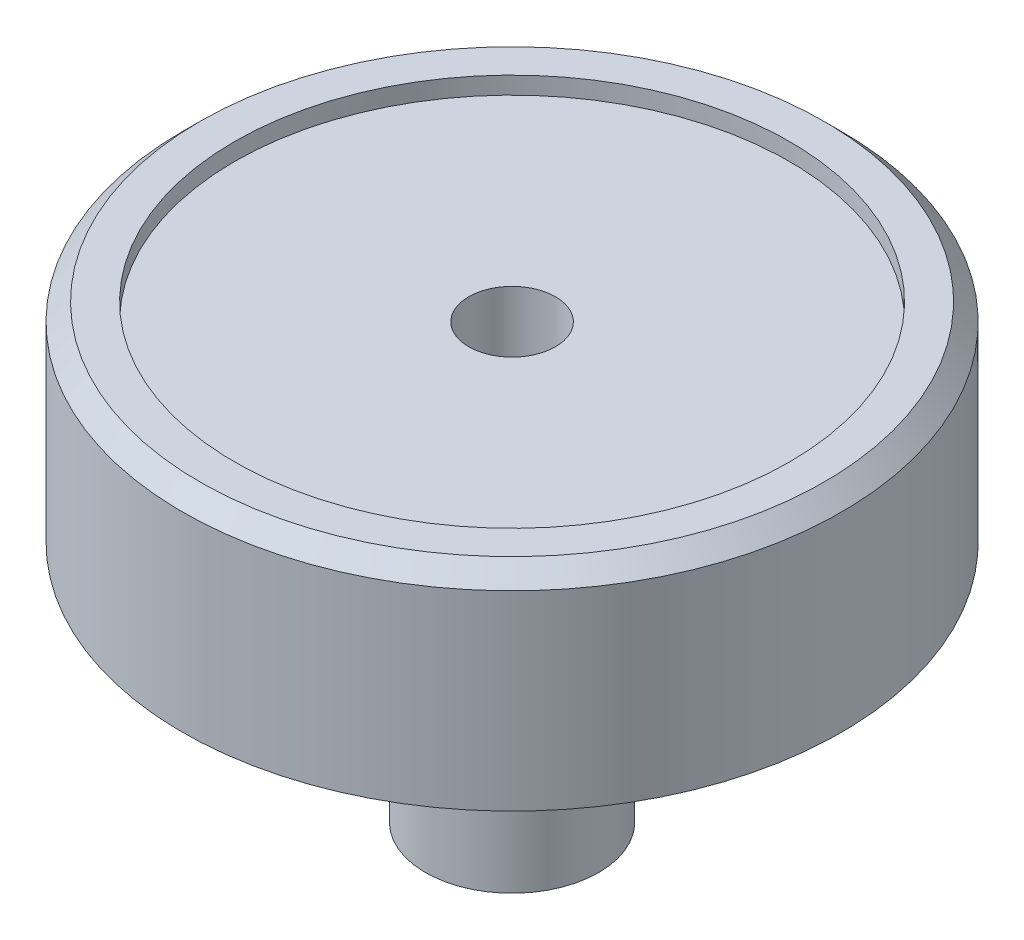
SolidWorks part; units mm, degrees
material "ABS"
ref_plane "Спереди" through (0, 0, 0) normal (0, 0, 1) x (1, 0, 0)
ref_plane "Сверху" through (0, 0, 0) normal (0, 1, 0) x (1, 0, 0)
ref_plane "Справа" through (0, 0, 0) normal (1, 0, 0) x (0, 0, -1)
sketch "Эскиз2" plane through (0, 0, 0) normal (0, 0, 1) x (1, 0, 0)
  line L1 (0, 4.5) -> (-9.5, 4.5)
  line L2 (-9.5, 4.5) -> (-9.5, -1.5)
  line L5 (-9.5, -1.5) -> (-6, -1.5)
  line L6 (-6, 0) -> (0, 0)
  line L7 (0, 4.5) -> (0, 0)
  line L8 (-6, -1.5) -> (-6, 0)
  dimension "D2" = 9.5
  dimension "D3" = 1.5
  dimension "D4" = 6
  dimension "D6" = 6
revolve "База" add sketch "Эскиз2" angle 360 about L7
chamfer "Фаска1" distance 0.5 angle 45 1 edges at (-9.5, 4.5, 0)
sketch "Эскиз8" plane through (0, 0, 0) normal (0, -1, 0) x (1, 0, 0)
  line L1 (-1.175, 3.175) -> (1.175, 3.175)
  line L2 (-3.175, 1.175) -> (-3.175, -1.175)
  line L3 (-1.175, -3.175) -> (1.175, -3.175)
  line L4 (3.175, 1.175) -> (3.175, -1.175)
  line L5 (-3.175, 3.175) -> (3.175, -3.175) construction
  line L6 (-3.175, -3.175) -> (3.175, 3.175) construction
  arc A0 (-3.175, -1.175) -> (-1.175, -3.175) centre (-1.175, -1.175) ccw
  arc A1 (1.175, -3.175) -> (3.175, -1.175) centre (1.175, -1.175) ccw
  arc A2 (1.175, 3.175) -> (3.175, 1.175) centre (1.175, 1.175) cw
  arc A3 (-1.175, 3.175) -> (-3.175, 1.175) centre (-1.175, 1.175) ccw
  point P0 (0, 0)
  dimension "D2" = 2
  dimension "D1" = 6.35
extrude "Направляющая" add sketch "Эскиз8" along normal blind 5.5
sketch "Эскиз6" plane through (0, 4.5, 0) normal (0, 1, 0) x (1, 0, 0)
  circle A0 centre (0, 0) radius 8
  dimension "D1" = 16
extrude "Основание пластины" cut sketch "Эскиз6" against normal blind 0.5
sketch "Эскиз9" plane through (0, -5.5, 0) normal (0, -1, 0) x (1, 0, 0)
  circle A0 centre (0, 0) radius 2.5
  dimension "D1" = 5
extrude "Продолжение направляющей" add sketch "Эскиз9" along normal blind 3
hole_wizard "Отверстие M2,5" positions "Эскиз4" profile "Эскиз5" tap size "M3" standard "ISO" end condition through all
sketch "Эскиз4" plane through (0, -8.5, 0) normal (0, -1, 0) x (-1, 0, 0)
  point P0 (0, 0)
sketch "Эскиз5" plane through (0, -8.5, 0) normal (1, 0, 0) x (0, 0, -1)
  line L0 (0, 0) -> (0, 13)
  line L1 (0, 13) -> (1.25, 13)
  line L2 (1.25, 13) -> (1.25, 0)
  line L5 (1.25, 0) -> (0, 0)
  line L11 (0, -6.35) -> (0, 107.95) construction
  dimension "Диаметр проходного сверла" = 2.5
  dimension "Глубина проходного сверла" = 13
cosmetic thread "Отверстие резьбы2" parameters "D2"=3
